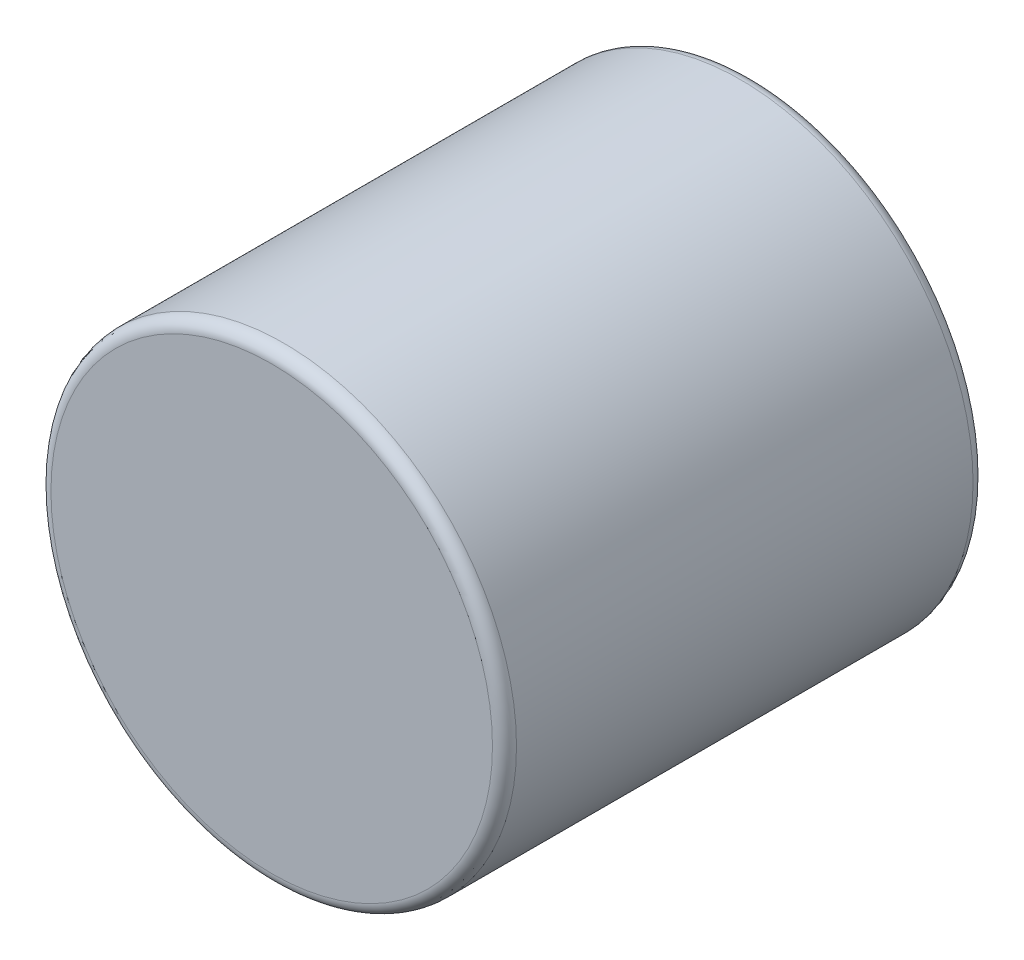
SolidWorks part; units mm, degrees
ref_plane "Front Plane" through (0, 0, 0) normal (0, 0, 1) x (1, 0, 0)
ref_plane "Top Plane" through (0, 0, 0) normal (0, 1, 0) x (1, 0, 0)
ref_plane "Right Plane" through (0, 0, 0) normal (1, 0, 0) x (0, 0, -1)
sketch "Sketch1" plane through (0, 0, 0) normal (0, 0, 1) x (1, 0, 0)
  circle A0 centre (0, 0) radius 49.2125
  dimension "D1" = 98.425
extrude "Boss-Extrude1" add sketch "Sketch1" along normal blind 101.6
fillet "Fillet1" radius 2.54 2 edges at (49.2125, 0, 0) (49.2125, 0, 101.6)
sketch "Sketch2" plane through (0, 0, 0) normal (0, 1, 0) x (1, 0, 0)
  line L0 (0, 0) -> (0, -99.06) construction
  line L1 (49.2125, -99.06) -> (-49.2125, -99.06) construction
